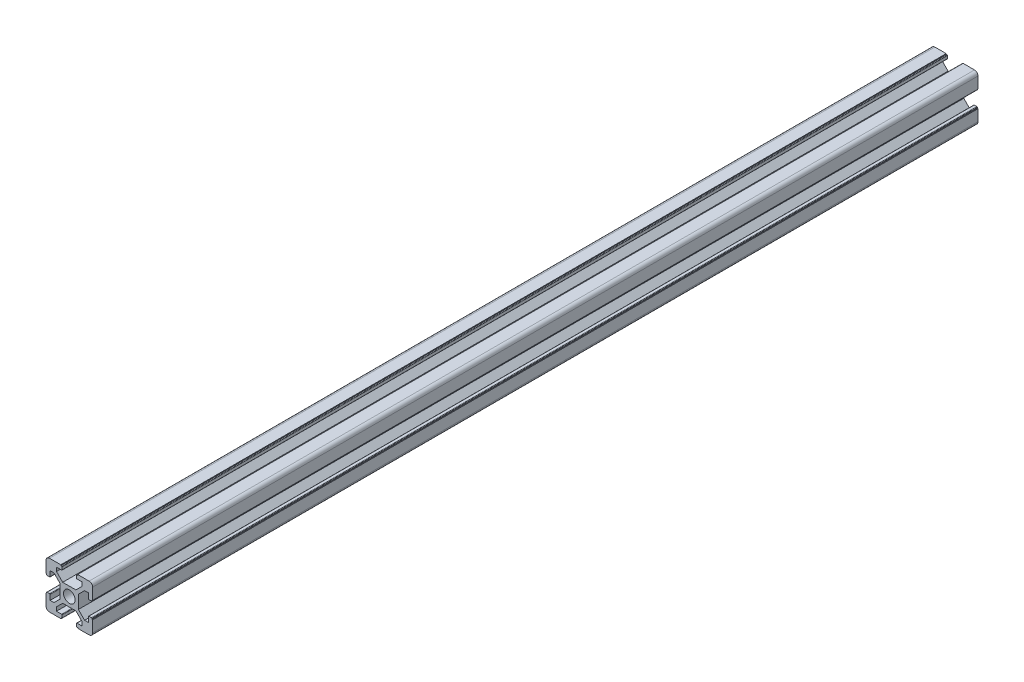
SolidWorks part; units mm, degrees
ref_plane "前视基准面" through (0, 0, 0) normal (0, 0, 1) x (1, 0, 0)
ref_plane "上视基准面" through (0, 0, 0) normal (0, 1, 0) x (1, 0, 0)
ref_plane "右视基准面" through (0, 0, 0) normal (1, 0, 0) x (0, 0, -1)
sketch "草图1" plane through (0, 0, 0) normal (0, 0, 1) x (1, 0, 0)
  line L0 (-17.5, 0) -> (33.5, 0) construction
  line L1 (0, 35.5833) -> (0, -31.0833) construction
  line L2 (3.65, 10) -> (8.5, 10)
  line L3 (10, 10) -> (10, -10) construction
  line L4 (-2.8393, 3.9) -> (2.8393, 3.9)
  line L5 (3.9, 2.8393) -> (3.9, -2.8393)
  line L6 (5.5, 8.2) -> (5.5, 6.5607)
  line L7 (3.9, 3.9) -> (10, 10) construction
  line L8 (4.4303, 3.3697) -> (6.5607, 5.5) construction
  line L9 (3.65, 10) -> (3.65, 8.2)
  line L10 (3.65, 8.2) -> (5.5, 8.2)
  line L11 (3.3697, 4.4303) -> (5.5, 6.5607) construction
  line L12 (5.5, 6.5607) -> (2.8393, 3.9)
  line L13 (6.5607, 5.5) -> (3.9, 2.8393)
  line L14 (3.3697, 4.4303) -> (9.4697, 10.5303) construction
  line L15 (4.4303, 3.3697) -> (10.5303, 9.4697) construction
  line L16 (8.2, 5.5) -> (6.5607, 5.5)
  line L17 (8.2, 3.65) -> (8.2, 5.5)
  line L18 (10, 3.65) -> (10, 8.5)
  line L19 (10, 3.65) -> (8.2, 3.65)
  line L20 (-3.3697, 4.4303) -> (-5.5, 6.5607) construction
  line L21 (-4.4303, 3.3697) -> (-6.5607, 5.5) construction
  line L22 (-3.9, 3.9) -> (-10, 10) construction
  line L23 (-10, 10) -> (-10, -10) construction
  line L24 (-10, 3.65) -> (-8.2, 3.65)
  line L25 (-10, 3.65) -> (-10, 8.5)
  line L26 (-8.2, 3.65) -> (-8.2, 5.5)
  line L27 (-8.2, 5.5) -> (-6.5607, 5.5)
  line L28 (-6.5607, 5.5) -> (-3.9, 2.8393)
  line L29 (-5.5, 6.5607) -> (-2.8393, 3.9)
  line L30 (-3.65, 8.2) -> (-5.5, 8.2)
  line L31 (-3.65, 10) -> (-3.65, 8.2)
  line L32 (-5.5, 8.2) -> (-5.5, 6.5607)
  line L33 (-3.9, 2.8393) -> (-3.9, -2.8393)
  line L34 (-3.65, 10) -> (-8.5, 10)
  line L35 (-3.9, -3.9) -> (-10, -10) construction
  line L36 (-4.4303, -3.3697) -> (-6.5607, -5.5) construction
  line L37 (-3.3697, -4.4303) -> (-5.5, -6.5607) construction
  line L38 (3.3697, -4.4303) -> (5.5, -6.5607) construction
  line L39 (4.4303, -3.3697) -> (6.5607, -5.5) construction
  line L40 (3.9, -3.9) -> (10, -10) construction
  line L41 (-3.65, -10) -> (-8.5, -10)
  line L42 (-5.5, -8.2) -> (-5.5, -6.5607)
  line L43 (-3.65, -10) -> (-3.65, -8.2)
  line L44 (-3.65, -8.2) -> (-5.5, -8.2)
  line L45 (-5.5, -6.5607) -> (-2.8393, -3.9)
  line L46 (-6.5607, -5.5) -> (-3.9, -2.8393)
  line L47 (-8.2, -5.5) -> (-6.5607, -5.5)
  line L48 (-8.2, -3.65) -> (-8.2, -5.5)
  line L49 (-10, -3.65) -> (-10, -8.5)
  line L50 (-10, -3.65) -> (-8.2, -3.65)
  line L51 (10, -3.65) -> (8.2, -3.65)
  line L52 (10, -3.65) -> (10, -8.5)
  line L53 (8.2, -3.65) -> (8.2, -5.5)
  line L54 (8.2, -5.5) -> (6.5607, -5.5)
  line L55 (6.5607, -5.5) -> (3.9, -2.8393)
  line L56 (5.5, -6.5607) -> (2.8393, -3.9)
  line L57 (3.65, -8.2) -> (5.5, -8.2)
  line L58 (3.65, -10) -> (3.65, -8.2)
  line L59 (5.5, -8.2) -> (5.5, -6.5607)
  line L60 (-2.8393, -3.9) -> (2.8393, -3.9)
  line L61 (3.65, -10) -> (8.5, -10)
  circle A0 centre (0, 0) radius 2.5
  arc A1 (-8.5, -10) -> (-10, -8.5) centre (-8.5, -8.5) cw
  arc A2 (10, -8.5) -> (8.5, -10) centre (8.5, -8.5) cw
  arc A3 (8.5, 10) -> (10, 8.5) centre (8.5, 8.5) cw
  arc A4 (-10, 8.5) -> (-8.5, 10) centre (-8.5, 8.5) cw
  point P13 (0, -3.9)
  point P42 (0, 3.9)
  point P43 (-10, 0)
  point P54 (10, 0)
  point P56 (-3.9, 0)
  point P70 (3.9, 0)
  dimension "D3" = 5
  dimension "D10" = 1.5
  dimension "D1" = 7.3
  dimension "D2" = 10
  dimension "D4" = 3.9
  dimension "D5" = 3.9
  dimension "D8" = 1.8
  dimension "D9" = 0.75
  dimension "D6" = 11
  dimension "D7" = 10
  dimension "D11" = 45
  dimension "D12" = 2.8393
extrude "凸台-拉伸2" add sketch "草图1" along normal blind 380 contours L34 A4 L25 L24 L26 L27 L28 L33 L46 L47 L48 L50 L49 A1 L41 L43 L44 L42 L45 L60 L56 L59 L57 L58 L61 A2 L52 L51 L53 L54 L55 L5 L13 L16 L17 L19 L18 A3 L2 L9 L10 L6 L12 L4 L29 L32 L30 L31
sketch "草图3" plane through (0, 0, 380) normal (0, 0, 1) x (1, 0, 0)
  line L0 (-12.6954, 0) -> (11.5012, 0) construction
  line L1 (0, 10.0863) -> (0, -11.0469) construction
  line L2 (-3.65, 8.2) -> (-3.3, 8.2)
  line L3 (3.65, 8.2) -> (3.6528, 8.2568)
  line L4 (-3.1, 8.4) -> (-3.1, 9.5)
  line L5 (3.65, 9.7) -> (3.65, 8.2)
  line L6 (-3.3, 9.7) -> (-3.65, 9.7)
  line L7 (-3.65, 8.2) -> (-3.65, 10) construction
  line L8 (-3.65, 9.7) -> (-3.65, 8.2)
  line L9 (-3.65, 8.2) -> (-3.6528, 8.2568)
  line L10 (3.3, 9.7) -> (3.65, 9.7)
  line L11 (3.1, 8.4) -> (3.1, 9.5)
  line L12 (3.65, 8.2) -> (3.3, 8.2)
  line L13 (3.65, -8.2) -> (3.3, -8.2)
  line L14 (3.1, -8.4) -> (3.1, -9.5)
  line L15 (3.3, -9.7) -> (3.65, -9.7)
  line L16 (-3.65, -8.2) -> (-3.6528, -8.2568)
  line L17 (-3.65, -9.7) -> (-3.65, -8.2)
  line L18 (-3.3, -9.7) -> (-3.65, -9.7)
  line L19 (3.65, -9.7) -> (3.65, -8.2)
  line L20 (-3.1, -8.4) -> (-3.1, -9.5)
  line L21 (3.65, -8.2) -> (3.6528, -8.2568)
  line L22 (-3.65, -8.2) -> (-3.3, -8.2)
  line L23 (0, 0) -> (9.5607, 9.5607) construction
  line L24 (-8.2, -3.65) -> (-8.2, -3.3)
  line L25 (-8.4, -3.1) -> (-9.5, -3.1)
  line L26 (-9.7, -3.3) -> (-9.7, -3.65)
  line L27 (-9.7, -3.65) -> (-8.2, -3.65)
  line L28 (-8.2, -3.65) -> (-8.2568, -3.6528)
  line L29 (8.2, 3.65) -> (8.2, 3.3)
  line L30 (8.4, 3.1) -> (9.5, 3.1)
  line L31 (9.7, 3.3) -> (9.7, 3.65)
  line L32 (9.7, 3.65) -> (8.2, 3.65)
  line L33 (8.2, 3.65) -> (8.2568, 3.6528)
  line L34 (-8.2, 3.65) -> (-8.2568, 3.6528)
  line L35 (-9.7, 3.65) -> (-8.2, 3.65)
  line L36 (-9.7, 3.3) -> (-9.7, 3.65)
  line L37 (-8.4, 3.1) -> (-9.5, 3.1)
  line L38 (-8.2, 3.65) -> (-8.2, 3.3)
  line L39 (8.2, -3.65) -> (8.2568, -3.6528)
  line L40 (9.7, -3.65) -> (8.2, -3.65)
  line L41 (9.7, -3.3) -> (9.7, -3.65)
  line L42 (8.4, -3.1) -> (9.5, -3.1)
  line L43 (8.2, -3.65) -> (8.2, -3.3)
  arc A0 (-3.1, 9.5) -> (-3.3, 9.7) centre (-3.3, 9.5) ccw
  arc A1 (-3.3, 8.2) -> (-3.1, 8.4) centre (-3.3, 8.4) ccw
  arc A2 (3.3, 8.2) -> (3.1, 8.4) centre (3.3, 8.4) cw
  arc A3 (3.1, 9.5) -> (3.3, 9.7) centre (3.3, 9.5) cw
  arc A4 (3.1, -9.5) -> (3.3, -9.7) centre (3.3, -9.5) ccw
  arc A5 (3.3, -8.2) -> (3.1, -8.4) centre (3.3, -8.4) ccw
  arc A6 (-3.3, -8.2) -> (-3.1, -8.4) centre (-3.3, -8.4) cw
  arc A7 (-3.1, -9.5) -> (-3.3, -9.7) centre (-3.3, -9.5) cw
  arc A8 (10, 8.5) -> (8.5, 10) centre (8.5, 8.5) ccw construction
  arc A9 (-9.5, -3.1) -> (-9.7, -3.3) centre (-9.5, -3.3) ccw
  arc A10 (-8.2, -3.3) -> (-8.4, -3.1) centre (-8.4, -3.3) ccw
  arc A11 (9.5, 3.1) -> (9.7, 3.3) centre (9.5, 3.3) ccw
  arc A12 (8.2, 3.3) -> (8.4, 3.1) centre (8.4, 3.3) ccw
  arc A13 (-8.2, 3.3) -> (-8.4, 3.1) centre (-8.4, 3.3) cw
  arc A14 (-9.5, 3.1) -> (-9.7, 3.3) centre (-9.5, 3.3) cw
  arc A15 (8.2, -3.3) -> (8.4, -3.1) centre (8.4, -3.3) cw
  arc A16 (9.5, -3.1) -> (9.7, -3.3) centre (9.5, -3.3) cw
  point P16 (-3.1, 9.7)
  point P19 (-3.1, 8.2)
  point P29 (3.1, 8.2)
  point P30 (3.1, 9.7)
  point P49 (3.1, -9.7)
  point P50 (3.1, -8.2)
  point P51 (-3.1, -8.2)
  point P52 (-3.1, -9.7)
  point P67 (-9.7, -3.1)
  point P68 (-8.2, -3.1)
  point P78 (9.7, 3.1)
  point P79 (8.2, 3.1)
  point P89 (-8.2, 3.1)
  point P90 (-9.7, 3.1)
  point P100 (8.2, -3.1)
  point P101 (9.7, -3.1)
  line M1 (-3.65, -10) -> (-3.65, -8.2)
  line M9 (3.65, -8.2) -> (3.65, -10)
  line M21 (8.2, 3.65) -> (10, 3.65)
  line M25 (3.65, 10) -> (3.65, 8.2)
  line M33 (-3.65, 8.2) -> (-3.65, 10)
  line M37 (-10, 3.65) -> (-8.2, 3.65)
  dimension "D3" = 0.2
  dimension "D1" = 6.2
  dimension "D2" = 1.5
extrude "凸台-拉伸3" add sketch "草图3" against normal blind 380 contours A14 L37 A13 L38 L36 M37 | L2 A1 L4 A0 L6 M33 | A3 L11 A2 L12 L10 M25 | L29 A12 L30 A11 L31 M21 | L13 A5 L14 A4 L15 M9 | A7 L20 A6 L22 L18 M1 | L43 A15 L42 A16 L41 L40 | L24 A10 L25 A9 L26 L27
